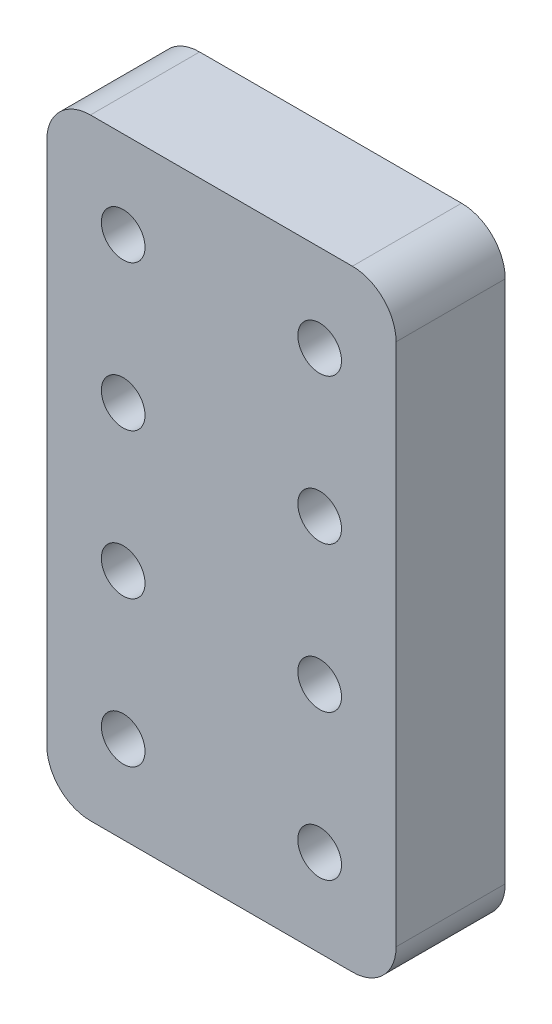
SolidWorks part; units mm, degrees
ref_plane "前视基准面" through (0, 0, 0) normal (0, 0, 1) x (1, 0, 0)
ref_plane "上视基准面" through (0, 0, 0) normal (0, 1, 0) x (1, 0, 0)
ref_plane "右视基准面" through (0, 0, 0) normal (1, 0, 0) x (0, 0, -1)
other "Configuration Table"
sketch "草图1" plane through (0, 0, 0) normal (0, 0, 1) x (1, 0, 0)
  line L0 (0, -55) -> (0, 55) construction
  line L1 (12, 28) -> (-12, 28)
  line L2 (16, 24) -> (16, -24)
  line L3 (12, -28) -> (-12, -28)
  line L4 (-16, 24) -> (-16, -24)
  line L5 (16, 28) -> (-16, -28) construction
  line L6 (16, -28) -> (-16, 28) construction
  circle A0 centre (9, 20) radius 2
  circle A1 centre (9, 6.6667) radius 2
  circle A2 centre (9, -6.6667) radius 2
  circle A3 centre (9, -20) radius 2
  circle A4 centre (-9, -20) radius 2
  circle A5 centre (-9, -6.6667) radius 2
  circle A6 centre (-9, 6.6667) radius 2
  circle A7 centre (-9, 20) radius 2
  arc A8 (-12, -28) -> (-16, -24) centre (-12, -24) cw
  arc A9 (16, -24) -> (12, -28) centre (12, -24) cw
  arc A10 (12, 28) -> (16, 24) centre (12, 24) cw
  arc A11 (-12, 28) -> (-16, 24) centre (-12, 24) ccw
  point P0 (0, 0)
  dimension "D2" = 9
  dimension "D3" = 4
  dimension "D4" = 8
  dimension "D7" = 8
  dimension "D8" = 4
  dimension "D1" = 32
  dimension "D5" = 56
  dimension "D6" = 4
extrude "凸台-拉伸1" add sketch "草图1" along normal blind 10
